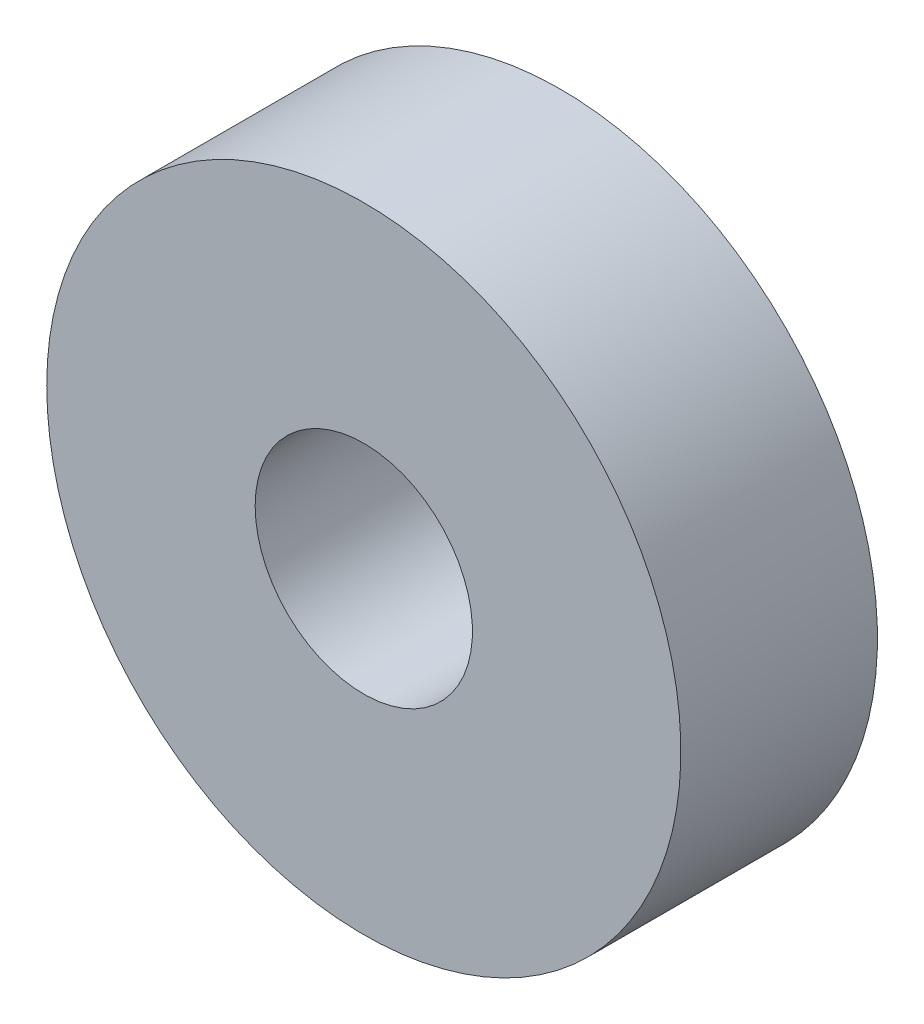
SolidWorks part; units mm, degrees
material "6061-T6 (SS)"
ref_plane "Front Plane" through (0, 0, 0) normal (0, 0, 1) x (1, 0, 0)
ref_plane "Top Plane" through (0, 0, 0) normal (0, 1, 0) x (1, 0, 0)
ref_plane "Right Plane" through (0, 0, 0) normal (1, 0, 0) x (0, 0, -1)
sketch "Sketch1" plane through (0, 0, 0) normal (1, 0, 0) x (0, 0, -1)
  line L0 (21.7309, 0) -> (-28.9169, 0) construction
  line L1 (-2.9527, 9.525) -> (-2.9527, 3.2639)
  line L2 (-2.9527, 9.525) -> (2.9527, 9.525)
  line L3 (-2.9527, 3.2639) -> (2.9527, 3.2639)
  line L4 (2.9527, 9.525) -> (2.9527, 3.2639)
  point P3 (0, 3.2639)
  dimension "D1" = 19.05
  dimension "D2" = 6.5278
  dimension "D3" = 5.9055
revolve "Revolve1" add sketch "Sketch1" angle 360 about L0
